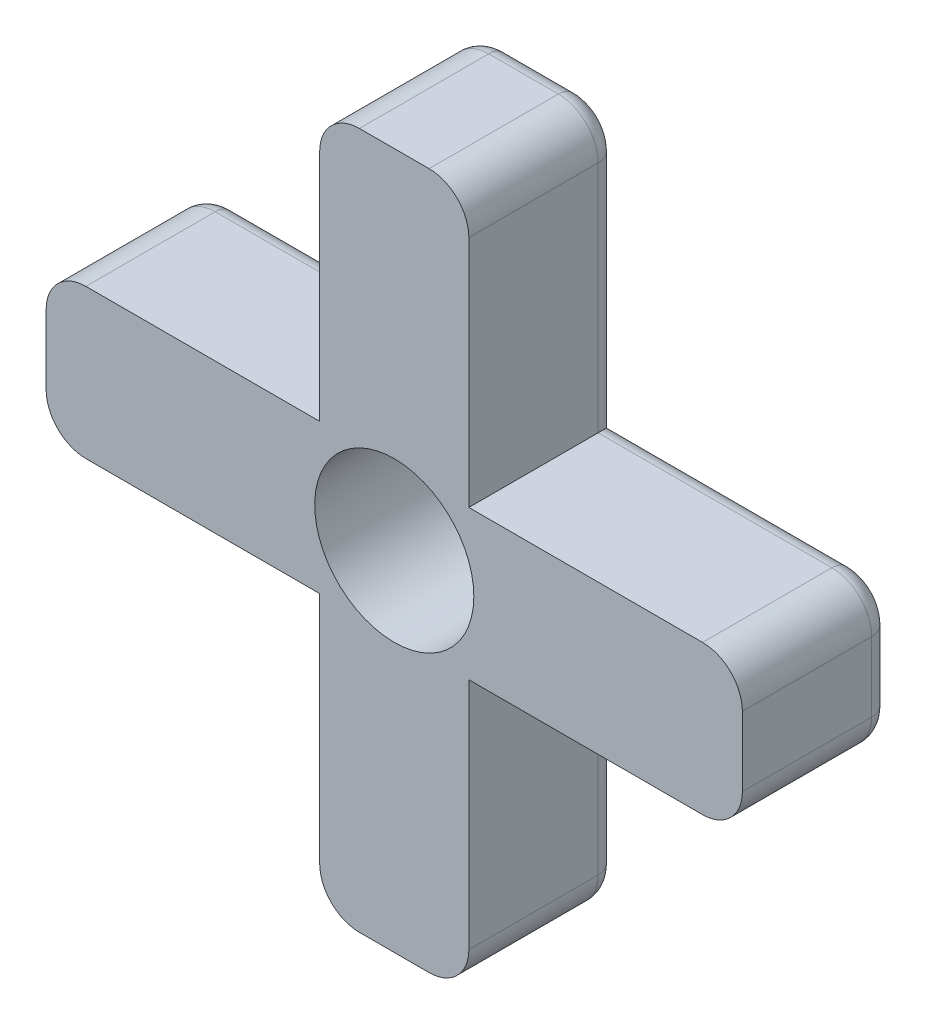
SolidWorks part; units mm, degrees
ref_plane "Front Plane" through (0, 0, 0) normal (0, 0, 1) x (1, 0, 0)
ref_plane "Top Plane" through (0, 0, 0) normal (0, 1, 0) x (1, 0, 0)
ref_plane "Right Plane" through (0, 0, 0) normal (1, 0, 0) x (0, 0, -1)
sketch "Sketch2" plane through (0, 0, 0) normal (0, 0, 1) x (1, 0, 0)
  line L1 (-75, 350) -> (75, 350)
  line L2 (-75, 350) -> (-75, 75)
  line L3 (-75, -350) -> (75, -350)
  line L4 (75, 350) -> (75, 75)
  line L7 (-350, 75) -> (-75, 75)
  line L8 (-350, 75) -> (-350, -75)
  line L9 (-350, -75) -> (-75, -75)
  line L10 (350, 75) -> (350, -75)
  line L14 (75, -75) -> (350, -75)
  line L16 (75, -75) -> (75, -350)
  line L18 (-75, -75) -> (-75, -350)
  line L19 (75, 75) -> (350, 75)
  point P0 (0, 0)
  point P6 (0, 0)
  dimension "D1" = 150
  dimension "D2" = 150
  dimension "D3" = 150
  dimension "D4" = 700
  dimension "D5" = 700
extrude "Boss-Extrude1" add sketch "Sketch2" along normal blind 150
fillet "Fillet1" radius 40 8 edges at (75, 350, 75) (-75, 350, 75) (-350, 75, 75) (-350, -75, 75) (-75, -350, 75) (75, -350, 75) (350, -75, 75) (350, 75, 75)
fillet "Fillet2" radius 20 20 edges at (-63.2843, 338.2843, 0) (-75, 192.5, 0) (-192.5, 75, 0) (-338.2843, 63.2843, 0) (-350, 0, 0) (-338.2843, -63.2843, 0) (-192.5, -75, 0) (-75, -192.5, 0) (-63.2843, -338.2843, 0) (0, -350, 0) (63.2843, -338.2843, 0) (75, -192.5, 0) (192.5, -75, 0) (338.2843, -63.2843, 0) (350, 0, 0) (338.2843, 63.2843, 0) (192.5, 75, 0) (75, 192.5, 0) (63.2843, 338.2843, 0) (0, 350, 0)
sketch "Sketch7" plane through (0, 0, 0) normal (0, 0, 1) x (1, 0, 0)
  circle A0 centre (0, 0) radius 80
  dimension "D1" = 160
extrude "Cut-Extrude1" cut sketch "Sketch7" along normal through all
